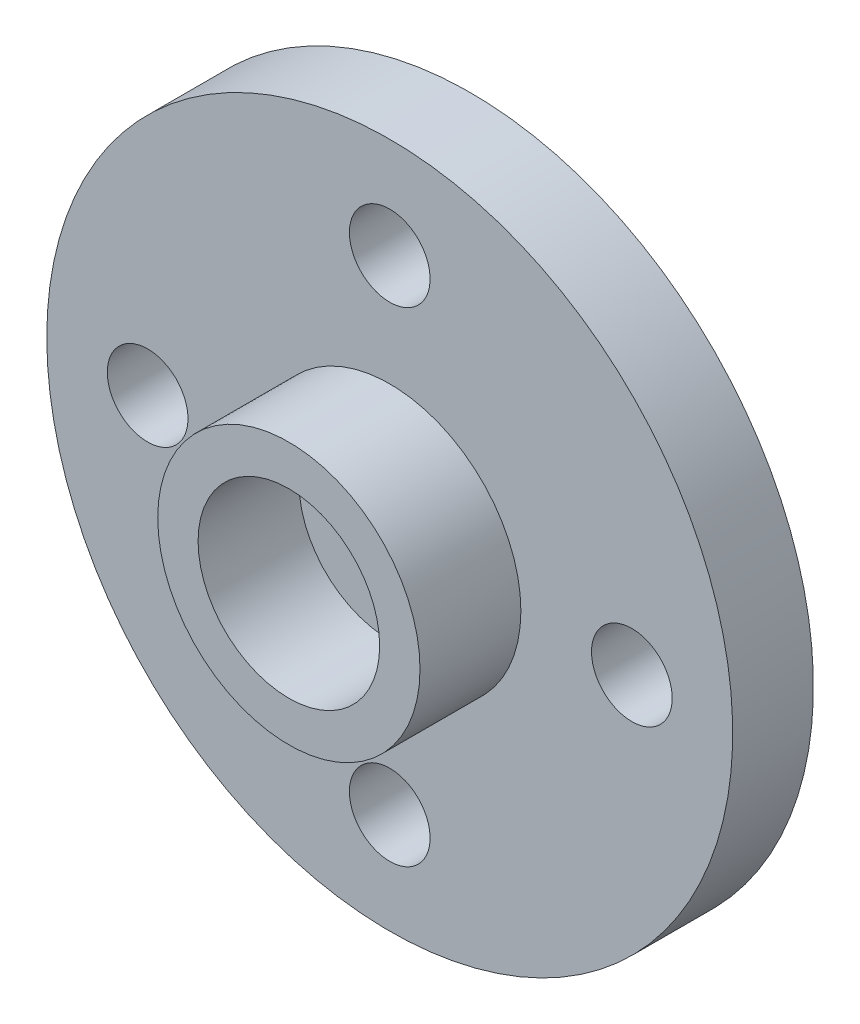
SolidWorks part; units mm, degrees
ref_plane "Front Plane" through (0, 0, 0) normal (0, 0, 1) x (1, 0, 0)
ref_plane "Top Plane" through (0, 0, 0) normal (0, 1, 0) x (1, 0, 0)
ref_plane "Right Plane" through (0, 0, 0) normal (1, 0, 0) x (0, 0, -1)
sketch "Sketch1" plane through (0, 0, 0) normal (0, 0, 1) x (1, 0, 0)
  circle A0 centre (0, 0) radius 2.25
  circle A1 centre (0, 0) radius 3.25
  dimension "D1" = 4.5
  dimension "D2" = 6.5
extrude "Boss-Extrude1" add sketch "Sketch1" along normal blind 4.5
sketch "Sketch2" plane through (0, 0, 0) normal (0, 0, -1) x (-1, 0, 0)
  line L0 (-8.692, 0) -> (8.8824, 0) construction
  circle A0 centre (0, 0) radius 8.5
  circle A1 centre (0, 0) radius 0.85
  circle A2 centre (-6, 0) radius 1
  circle A3 centre (0, 6) radius 1
  circle A4 centre (6, 0) radius 1
  circle A5 centre (0, -6) radius 1
  point P17 (0, 0)
  dimension "D1" = 17
  dimension "D2" = 1.7
  dimension "D3" = 2
  dimension "D4" = 6
  dimension "D5" = 4
extrude "Boss-Extrude2" add sketch "Sketch2" against normal blind 2
